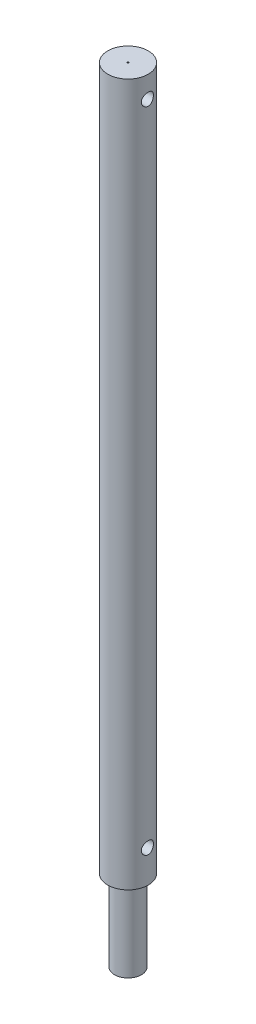
SolidWorks part; units mm, degrees
ref_plane "Plan de face" through (0, 0, 0) normal (0, 0, 1) x (1, 0, 0)
ref_plane "Plan de dessus" through (0, 0, 0) normal (0, 1, 0) x (1, 0, 0)
ref_plane "Plan de droite" through (0, 0, 0) normal (1, 0, 0) x (0, 0, -1)
sketch "Esquisse1" plane through (0, 0, 0) normal (0, 1, 0) x (1, 0, 0)
  circle A0 centre (0, 0) radius 15
extrude "Boss.-Extru.1" add sketch "Esquisse1" along normal blind 650
sketch "Esquisse2" plane through (0, 0, 0) normal (0, -1, 0) x (-1, 0, 0)
  circle A0 centre (0, 0) radius 10
  circle A1 centre (0, 0) radius 15
extrude "Enlèv. mat.-Extru.1" cut sketch "Esquisse2" against normal blind 60
sketch "Esquisse3" plane through (0, 0, 0) normal (0, -1, 0) x (-1, 0, 0)
  circle A0 centre (0, 0) radius 2
extrude "Enlèv. mat.-Extru.2" cut sketch "Esquisse3" against normal blind 50
hole_wizard "Dégagement M81" positions "Esquisse3D2" profile "Esquisse5" hole size "M8" standard "ISO" end condition through all
sketch3d "Esquisse3D2"
  point P0 (-15, 84, 0)
  point P2 (-15, 564, 0)
sketch "Esquisse5" plane through (-15, 84, 0) normal (0, 1, 0) x (0, 0, 1)
  line L0 (0, 0) -> (0, 30)
  line L1 (0, 30) -> (4.5, 30)
  line L2 (4.5, 30) -> (4.5, 0)
  line L5 (4.5, 0) -> (0, 0)
  line L11 (0, -6.35) -> (0, 107.95) construction
  dimension "Diamètre du perçage jusqu'au prochain" = 9
  dimension "Profondeur du perçage jusqu'au prochain" = 30
sketch "Esquisse6" plane through (0, 650, 0) normal (0, 1, 0) x (1, 0, 0)
  circle A0 centre (0, 0) radius 0.5
extrude "Enlèv. mat.-Extru.3" cut sketch "Esquisse6" against normal blind 580
sketch "Esquisse7" plane through (0, 650, 0) normal (0, 1, 0) x (1, 0, 0)
  circle A0 centre (0, 0) radius 15
extrude "Enlèv. mat.-Extru.4" cut sketch "Esquisse7" against normal blind 70
